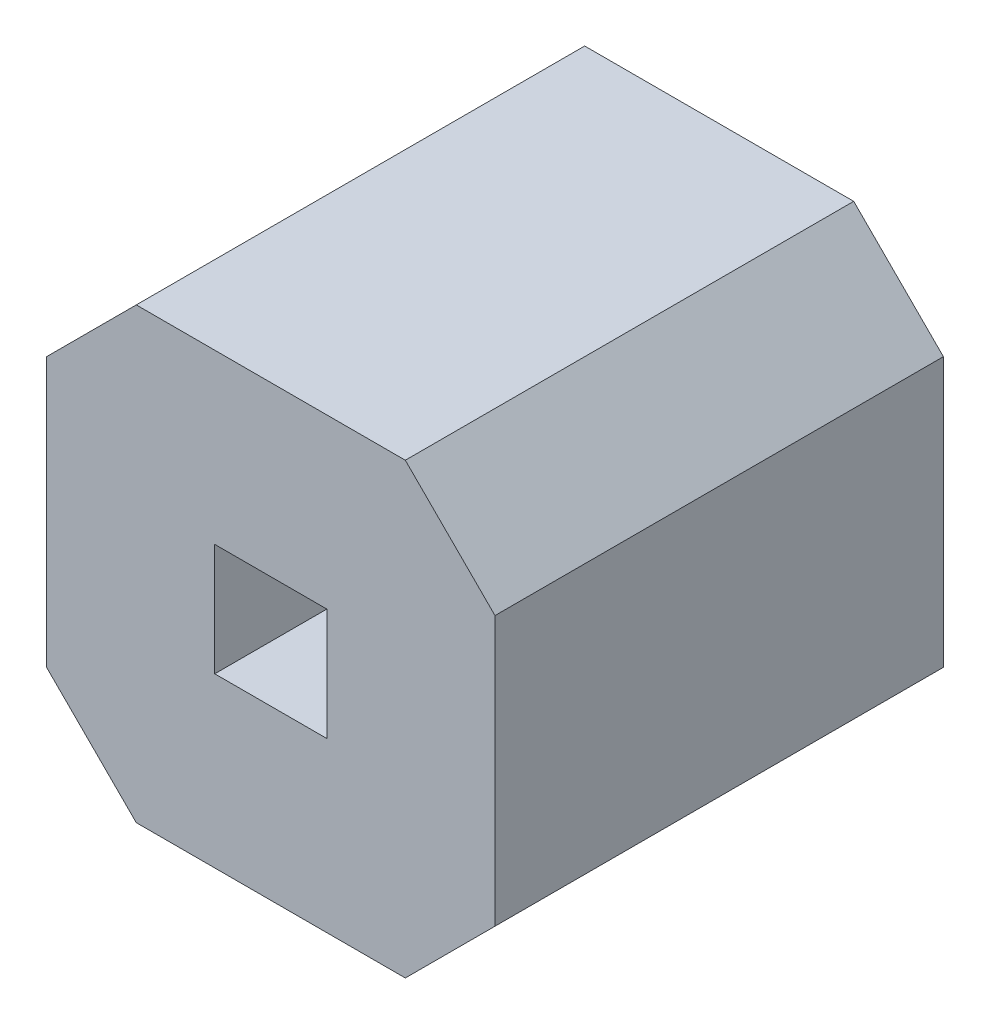
SolidWorks part; units mm, degrees
material "Nylon 6/10"
ref_plane "Front Plane" through (0, 0, 0) normal (0, 0, 1) x (1, 0, 0)
ref_plane "Top Plane" through (0, 0, 0) normal (0, 1, 0) x (1, 0, 0)
ref_plane "Right Plane" through (0, 0, 0) normal (1, 0, 0) x (0, 0, -1)
sketch "Sketch1" plane through (0, 0, 0) normal (0, 0, 1) x (1, 0, 0)
  line L0 (2.032, 2.54) -> (2.54, 2.032)
  line L1 (0.508, 0) -> (2.032, 0)
  line L2 (0, 0.508) -> (0, 2.032)
  line L3 (0.508, 2.54) -> (2.032, 2.54)
  line L4 (2.54, 0.508) -> (2.54, 2.032)
  line L5 (0, 2.032) -> (0.508, 2.54)
  line L6 (0, 0.508) -> (0.508, 0)
  line L7 (2.032, 0) -> (2.54, 0.508)
  line L8 (0.508, 2.54) -> (2.032, 0) construction
  line L10 (0.9525, 0.9525) -> (1.5875, 0.9525)
  line L11 (0.9525, 0.9525) -> (0.9525, 1.5875)
  line L12 (0.9525, 1.5875) -> (1.5875, 1.5875)
  line L13 (1.5875, 0.9525) -> (1.5875, 1.5875)
  line L14 (0.9525, 0.9525) -> (1.5875, 1.5875) construction
  line L15 (0.9525, 1.5875) -> (1.5875, 0.9525) construction
  point P0 (0, 0)
  point P1 (2.54, 2.54)
  point P2 (0, 2.54)
  point P3 (2.54, 0)
  point P13 (1.27, 1.27)
  point P14 (1.27, 1.27)
  dimension "D1" = 2.54
  dimension "D2" = 2.54
  dimension "D3" = 0.635
extrude "Boss-Extrude1" add sketch "Sketch1" along normal blind 2.54
